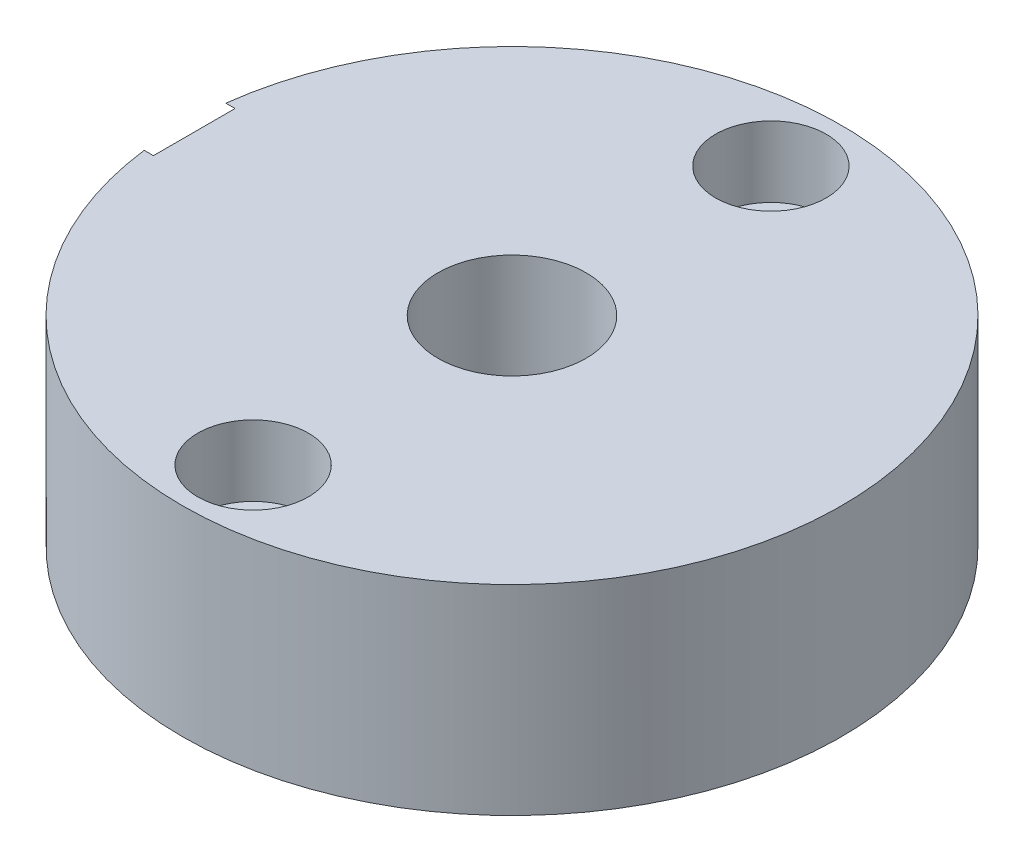
SolidWorks part; units mm, degrees
material "6061-T6 (SS)"
ref_plane "Front Plane" through (0, 0, 0) normal (0, 0, 1) x (1, 0, 0)
ref_plane "Top Plane" through (0, 0, 0) normal (0, 1, 0) x (1, 0, 0)
ref_plane "Right Plane" through (0, 0, 0) normal (1, 0, 0) x (0, 0, -1)
ref_plane "Plane1" through (0, 0, 0) normal (0, 0, -1) x (-1, 0, 0)
sketch "Sketch1" plane through (0, 0, 0) normal (0, 0, -1) x (-1, 0, 0)
  line L0 (-14.224, 0) -> (0, 0)
  line L1 (0, 0) -> (0, 8.636)
  line L2 (0, 8.636) -> (-14.224, 8.636)
  line L3 (-14.224, 8.636) -> (-14.224, 0)
  line L4 (0, 0) -> (0, 8.636) construction
revolve "Revolve1" add sketch "Sketch1" angle 360 about L4
hole_wizard "CBORE for M2.5 Hex Head Machine Screw1" positions "Sketch3" profile "Sketch2" counterbore size "M2.5" standard "ANSI Metric"
sketch "Sketch3" plane through (0, 8.636, 0) normal (0, 1, 0) x (1, 0, 0)
  point P0 (0, -11.176)
  point P1 (0, 11.176)
sketch "Sketch2" plane through (0, 8.636, 11.176) normal (1, 0, 0) x (0, 0, 1)
  line L0 (0, 0) -> (0, 8.636)
  line L1 (0, 8.636) -> (1.524, 8.636)
  line L3 (1.524, 8.636) -> (1.524, 3.048)
  line L4 (1.524, 3.048) -> (2.3876, 3.048)
  line L5 (2.3876, 3.048) -> (2.3876, 0)
  line L7 (2.3876, 0) -> (0, 0)
  line L11 (0, -6.35) -> (0, 107.95) construction
  dimension "Thru Hole Dia." = 3.048
  dimension "Thru Hole Depth" = 8.636
  dimension "C'Bore Dia." = 4.7752
  dimension "C'Bore Depth" = 3.048
hole_wizard "M2.5 Clearance Hole1" positions "Sketch5" profile "Sketch4" hole size "M2.5" standard "ANSI Metric"
sketch "Sketch5" plane through (0, 0, 0) normal (0, -1, 0) x (-1, 0, 0)
  point P0 (-7.9026, 7.9026)
  point P1 (7.9026, -7.9026)
  point P2 (-7.9026, -7.9026)
  point P3 (7.9026, 7.9026)
sketch "Sketch4" plane through (7.9026, 0, -7.9026) normal (1, 0, 0) x (0, 0, -1)
  line L0 (0, 0) -> (0, 2.54)
  line L1 (0, 2.54) -> (1.524, 2.54)
  line L2 (1.524, 2.54) -> (1.524, 0)
  line L5 (1.524, 0) -> (0, 0)
  line L10 (0, 2.54) -> (-1.524, 2.54) construction
  line L11 (0, -6.35) -> (0, 107.95) construction
  dimension "Hole Dia." = 3.048
  dimension "Hole Depth" = 2.54
  dimension "Drill Angle" = 180
hole_wizard "CBORE for M6 Hex Head Bolt1" positions "Sketch7" profile "Sketch6" counterbore size "M6" standard "ANSI Metric"
sketch "Sketch7" plane through (0, 0, 0) normal (0, -1, 0) x (-1, 0, 0)
  point P0 (0, 0)
sketch "Sketch6" plane through (0, 0, 0) normal (1, 0, 0) x (0, 0, -1)
  line L0 (0, 0) -> (0, 8.636)
  line L1 (0, 8.636) -> (3.2004, 8.636)
  line L3 (3.2004, 8.636) -> (3.2004, 2.54)
  line L4 (3.2004, 2.54) -> (7.747, 2.54)
  line L5 (7.747, 2.54) -> (7.747, 0)
  line L7 (7.747, 0) -> (0, 0)
  line L11 (0, -6.35) -> (0, 107.95) construction
  dimension "Thru Hole Dia." = 6.4008
  dimension "Thru Hole Depth" = 8.636
  dimension "C'Bore Dia." = 15.494
  dimension "C'Bore Depth" = 2.54
hole_wizard "CBORE for M3.5 Hex Head Machine Screw1" positions "3DSketch1" profile "Sketch8" counterbore size "M3.5" standard "ANSI Metric"
sketch3d "3DSketch1"
  point P0 (-14.224, 5.08, 0)
sketch "Sketch8" plane through (-14.224, 5.08, 0) normal (0, 1, 0) x (0, 0, 1)
  line L0 (0, 0) -> (0, 8.2573)
  line L1 (0, 8.2573) -> (1.9837, 7.112)
  line L2 (1.9837, 7.112) -> (1.9837, 0.508)
  line L3 (1.9837, 0.508) -> (3.9687, 0.508)
  line L4 (3.9687, 0.508) -> (3.9687, 0)
  line L5 (3.9687, 0) -> (0, 0)
  line L10 (0, 8.2573) -> (-1.9837, 7.112) construction
  line L11 (0, -6.35) -> (0, 107.95) construction
  dimension "Hole Dia." = 3.9675
  dimension "Hole Depth" = 7.112
  dimension "C'Bore Dia." = 7.9375
  dimension "C'Bore Depth" = 0.508
  dimension "Drill Angle" = 120
chamfer "Chamfer1" distance 0.4293 angle 45 1 edges at (-13.716, 5.08, 1.9837)
